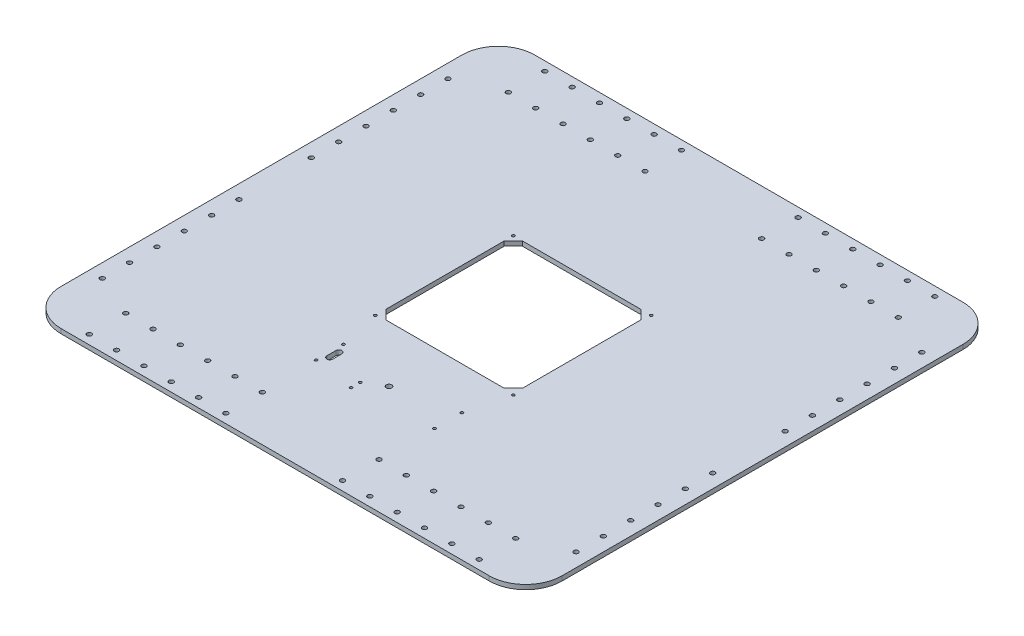
SolidWorks part; units mm, degrees
ref_plane "Front Plane" through (0, 0, 0) normal (0, 0, 1) x (1, 0, 0)
ref_plane "Top Plane" through (0, 0, 0) normal (0, 1, 0) x (1, 0, 0)
ref_plane "Right Plane" through (0, 0, 0) normal (1, 0, 0) x (0, 0, -1)
sketch "Sketch1" plane through (0, 0, 0) normal (0, 1, 0) x (1, 0, 0)
  line L0 (275, 520) -> (275, 0) construction
  line L1 (40, 0) -> (510, 0)
  line L2 (0, 40) -> (0, 480)
  line L3 (40, 520) -> (510, 520)
  line L4 (550, 40) -> (550, 480)
  line L5 (0, 260) -> (550, 260) construction
  line L6 (200, 326.4564) -> (210, 336.4564)
  line L7 (210, 336.4564) -> (340, 336.4564)
  line L8 (200, 326.4564) -> (200, 196.4564)
  line L9 (210, 186.4564) -> (340, 186.4564)
  line L10 (350, 326.4564) -> (350, 196.4564)
  line L11 (200, 336.4564) -> (350, 186.4564) construction
  line L12 (200, 186.4564) -> (350, 336.4564) construction
  line L13 (340, 336.4564) -> (350, 326.4564)
  line L14 (340, 186.4564) -> (350, 196.4564)
  line L15 (200, 196.4564) -> (210, 186.4564)
  line L17 (255.4058, 103) -> (255.4058, 113) construction
  line L19 (218.2203, 120) -> (218.2203, 130)
  line L25 (205, 100) -> (345, 100) construction
  line L26 (211.7797, 130) -> (211.7797, 120)
  arc A0 (40, 0) -> (0, 40) centre (40, 40) cw
  arc A1 (510, 0) -> (550, 40) centre (510, 40) ccw
  arc A2 (510, 520) -> (550, 480) centre (510, 480) cw
  arc A3 (0, 480) -> (40, 520) centre (40, 480) cw
  circle A6 centre (275, 125) radius 3
  circle A9 centre (200, 336.4564) radius 1.5
  circle A10 centre (351.4564, 336.4564) radius 1.5
  circle A11 centre (351.4564, 185) radius 1.5
  circle A12 centre (200, 185) radius 1.5
  circle A15 centre (255.4058, 113) radius 1.5
  circle A16 centre (210, 110) radius 1.5
  circle A18 centre (255.4058, 103) radius 1.5
  circle A19 centre (340, 140) radius 1.5
  circle A21 centre (210, 140) radius 1.5
  circle A23 centre (340, 110) radius 1.5
  arc A25 (211.7797, 120) -> (218.2203, 120) centre (215, 120) ccw
  arc A26 (218.2203, 130) -> (211.7797, 130) centre (215, 130) ccw
  point P7 (0, 0)
  point P10 (550, 0)
  point P15 (0, 520)
  point P22 (275, 261.4564)
  point P47 (275.7282, 260.7282)
  dimension "D3" = 3
  dimension "D4" = 3
  dimension "D5" = 3
  dimension "D6" = 3
  dimension "D7" = 3
  dimension "D8" = 6
  dimension "D16" = 1.4564
  dimension "D17" = 10
  dimension "D18" = 3
  dimension "D19" = 45
  dimension "D20" = 0.7282
  dimension "D1" = 3
  dimension "D2" = 3
  dimension "D9" = 3
  dimension "D10" = 40
  dimension "D11" = 3.2203
  dimension "D12" = 550
  dimension "D13" = 0.7282
  dimension "D14" = 110
  dimension "D15" = 10
  dimension "D21" = 3
  dimension "D22" = 3
  dimension "D23" = 10
  dimension "D24" = 136.4564
extrude "Boss-Extrude1" add sketch "Sketch1" along normal blind 5
sketch "Sketch4" plane through (0, 5, 0) normal (0, 1, 0) x (1, 0, 0)
  line L5 (550, 40) -> (550, 480) construction
  line L6 (275, 520) -> (275, 0) construction
  line L7 (510, 520) -> (40, 520) construction
  line L8 (40, 0) -> (510, 0) construction
  line L9 (0, 260) -> (550, 260) construction
  line L10 (0, 480) -> (0, 40) construction
  circle A2 centre (535, 70.2663) radius 2.5
  circle A10 centre (488.9946, 10) radius 2.5
  circle A11 centre (488.9946, 50) radius 2.5
  circle A12 centre (535, 100.2663) radius 2.5
  circle A13 centre (535, 130.2663) radius 2.5
  circle A14 centre (535, 160.2663) radius 2.5
  circle A15 centre (535, 190.2663) radius 2.5
  circle A16 centre (535, 220.2663) radius 2.5
  circle A17 centre (458.9946, 50) radius 2.5
  circle A18 centre (458.9946, 10) radius 2.5
  circle A19 centre (428.9946, 50) radius 2.5
  circle A20 centre (428.9946, 10) radius 2.5
  circle A21 centre (398.9946, 50) radius 2.5
  circle A22 centre (398.9946, 10) radius 2.5
  circle A23 centre (368.9946, 50) radius 2.5
  circle A24 centre (368.9946, 10) radius 2.5
  circle A25 centre (338.9946, 50) radius 2.5
  circle A26 centre (338.9946, 10) radius 2.5
  circle A27 centre (338.9946, 510) radius 2.5
  circle A28 centre (338.9946, 470) radius 2.5
  circle A29 centre (368.9946, 510) radius 2.5
  circle A30 centre (368.9946, 470) radius 2.5
  circle A31 centre (398.9946, 510) radius 2.5
  circle A32 centre (398.9946, 470) radius 2.5
  circle A33 centre (428.9946, 510) radius 2.5
  circle A34 centre (428.9946, 470) radius 2.5
  circle A35 centre (458.9946, 510) radius 2.5
  circle A36 centre (458.9946, 470) radius 2.5
  circle A37 centre (535, 299.7337) radius 2.5
  circle A38 centre (535, 329.7337) radius 2.5
  circle A39 centre (535, 359.7337) radius 2.5
  circle A40 centre (535, 389.7337) radius 2.5
  circle A41 centre (535, 419.7337) radius 2.5
  circle A42 centre (488.9946, 470) radius 2.5
  circle A43 centre (488.9946, 510) radius 2.5
  circle A44 centre (535, 449.7337) radius 2.5
  circle A45 centre (211.0054, 10) radius 2.5
  circle A46 centre (211.0054, 50) radius 2.5
  circle A47 centre (181.0054, 10) radius 2.5
  circle A48 centre (181.0054, 50) radius 2.5
  circle A49 centre (151.0054, 10) radius 2.5
  circle A50 centre (151.0054, 50) radius 2.5
  circle A51 centre (121.0054, 10) radius 2.5
  circle A52 centre (121.0054, 50) radius 2.5
  circle A53 centre (91.0054, 10) radius 2.5
  circle A54 centre (91.0054, 50) radius 2.5
  circle A55 centre (15, 220.2663) radius 2.5
  circle A56 centre (15, 190.2663) radius 2.5
  circle A57 centre (15, 160.2663) radius 2.5
  circle A58 centre (15, 130.2663) radius 2.5
  circle A59 centre (15, 100.2663) radius 2.5
  circle A60 centre (61.0054, 50) radius 2.5
  circle A61 centre (61.0054, 10) radius 2.5
  circle A62 centre (15, 70.2663) radius 2.5
  circle A63 centre (15, 449.7337) radius 2.5
  circle A64 centre (61.0054, 510) radius 2.5
  circle A65 centre (61.0054, 470) radius 2.5
  circle A66 centre (15, 419.7337) radius 2.5
  circle A67 centre (15, 389.7337) radius 2.5
  circle A68 centre (15, 359.7337) radius 2.5
  circle A69 centre (15, 329.7337) radius 2.5
  circle A70 centre (15, 299.7337) radius 2.5
  circle A71 centre (91.0054, 470) radius 2.5
  circle A72 centre (91.0054, 510) radius 2.5
  circle A73 centre (121.0054, 470) radius 2.5
  circle A74 centre (121.0054, 510) radius 2.5
  circle A75 centre (151.0054, 470) radius 2.5
  circle A76 centre (151.0054, 510) radius 2.5
  circle A77 centre (181.0054, 470) radius 2.5
  circle A78 centre (181.0054, 510) radius 2.5
  circle A79 centre (211.0054, 470) radius 2.5
  circle A80 centre (211.0054, 510) radius 2.5
  dimension "D1" = 5
  dimension "D2" = 5
  dimension "D3" = 5
  dimension "D7" = 6
  dimension "5" = 5
  dimension "D8" = 6
extrude "Cut-Extrude1" cut sketch "Sketch4" against normal through all
